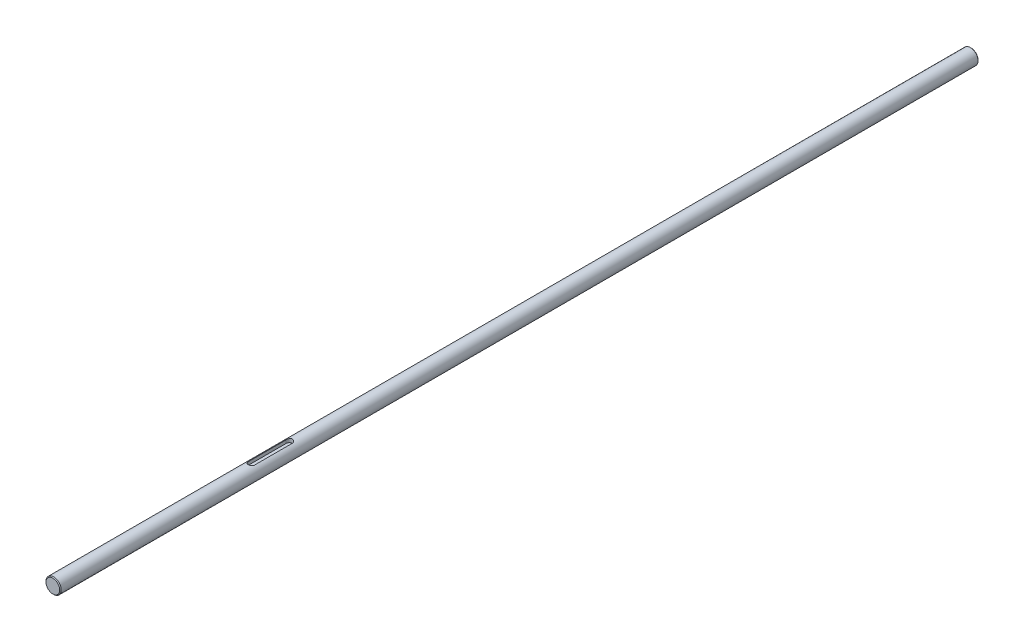
SolidWorks part; units mm, degrees
ref_plane "前视基准面" through (0, 0, 0) normal (0, 0, 1) x (1, 0, 0)
ref_plane "上视基准面" through (0, 0, 0) normal (0, 1, 0) x (1, 0, 0)
ref_plane "右视基准面" through (0, 0, 0) normal (1, 0, 0) x (0, 0, -1)
sketch "草图1" plane through (0, 0, 0) normal (0, 0, 1) x (1, 0, 0)
  circle A0 centre (0, 0) radius 5
  dimension "D1" = 10
extrude "拉伸1" add sketch "草图1" along normal blind 602
chamfer "倒角1" distance 0.5 angle 45 2 edges at (5, 0, 602) (5, 0, 0)
ref_plane "基准面1" through (0, 2.5, 0) normal (0, 1, 0) x (-1, 0, 0)
sketch "草图2" plane through (0, 2.5, 0) normal (0, 1, 0) x (-1, 0, 0)
  line L0 (0, 601.5) -> (0, 0) construction
  line L1 (-5, 601.5) -> (5, 601.5) construction
  line L2 (4.5, 602) -> (-4.5, 602) construction
  line L3 (2, 472) -> (-2, 472) construction
  line L4 (2, 472) -> (2, 447)
  line L5 (2, 447) -> (-2, 447) construction
  line L6 (-2, 472) -> (-2, 447)
  line L7 (2, 472) -> (-2, 447) construction
  line L8 (2, 447) -> (-2, 472) construction
  arc A0 (-2, 472) -> (2, 472) centre (0, 472) cw
  arc A1 (-2, 447) -> (2, 447) centre (0, 447) ccw
  point P5 (0, 459.5)
  dimension "D1" = 130
  dimension "D2" = 25
  dimension "D3" = 4
extrude "拉伸2" cut sketch "草图2" along normal blind 10
